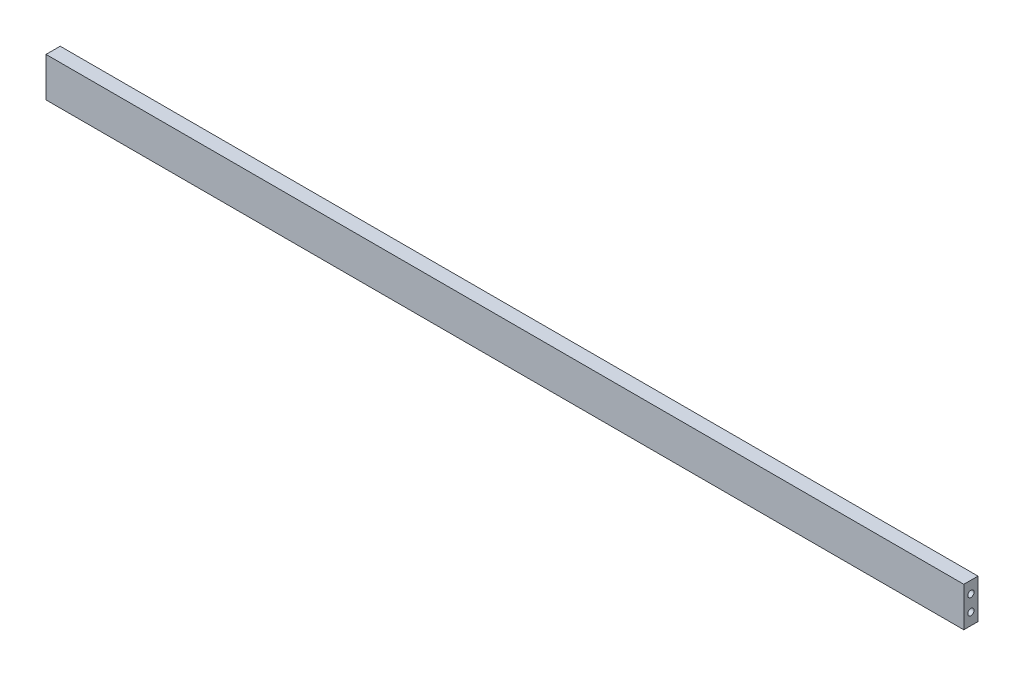
SolidWorks part; units mm, degrees
ref_plane "Front Plane" through (0, 0, 0) normal (0, 0, 1) x (1, 0, 0)
ref_plane "Top Plane" through (0, 0, 0) normal (0, 1, 0) x (1, 0, 0)
ref_plane "Right Plane" through (0, 0, 0) normal (1, 0, 0) x (0, 0, -1)
ref_plane "Back Plane" through (0, 0, -18) normal (0, 0, 1) x (1, 0, 0)
ref_plane "Bottom Plane" through (0, -50, 0) normal (0, 1, 0) x (-1, 0, 0)
ref_plane "Left Plane" through (-1164, 0, 0) normal (1, 0, 0) x (0, 0, -1)
sketch "Sketch1" plane through (0, -50, 0) normal (0, 1, 0) x (-1, 0, 0)
  line L0 (1164, 55) -> (1164, -55) construction
  line L1 (1164, -18) -> (0, -18)
  line L2 (1164, -18) -> (1164, 0)
  line L3 (1164, 0) -> (0, 0)
  line L4 (0, -18) -> (0, 0)
  line L5 (55, -18) -> (-55, -18) construction
  line L7 (0, 55) -> (0, -55) construction
  line L8 (55, 0) -> (-55, 0) construction
extrude "Plinth" add sketch "Sketch1" along normal up to surface (50 mm away) up to plane "Top Plane"
sketch "Sketch2" plane through (0, 0, 0) normal (1, 0, 0) x (0, 0, -1)
  line L0 (9, 0) -> (9, -50) construction
  line L1 (0, 0) -> (18, 0) construction
  line L2 (0, -50) -> (18, -50) construction
  circle A0 centre (9, -15) radius 4
  circle A1 centre (9, -35) radius 4
  dimension "D3" = 8
  dimension "D1" = 15
  dimension "D2" = 15
extrude "Extrude1" cut sketch "Sketch2" against normal blind 10
sketch "Sketch3" plane through (-1164, 0, 0) normal (1, 0, 0) x (0, 0, -1)
  circle A0 centre (9, -35) radius 4 construction
  circle A1 centre (9, -15) radius 4 construction
  circle A2 centre (9, -35) radius 4
  circle A3 centre (9, -15) radius 4
extrude "Extrude2" cut sketch "Sketch3" along normal blind 10
